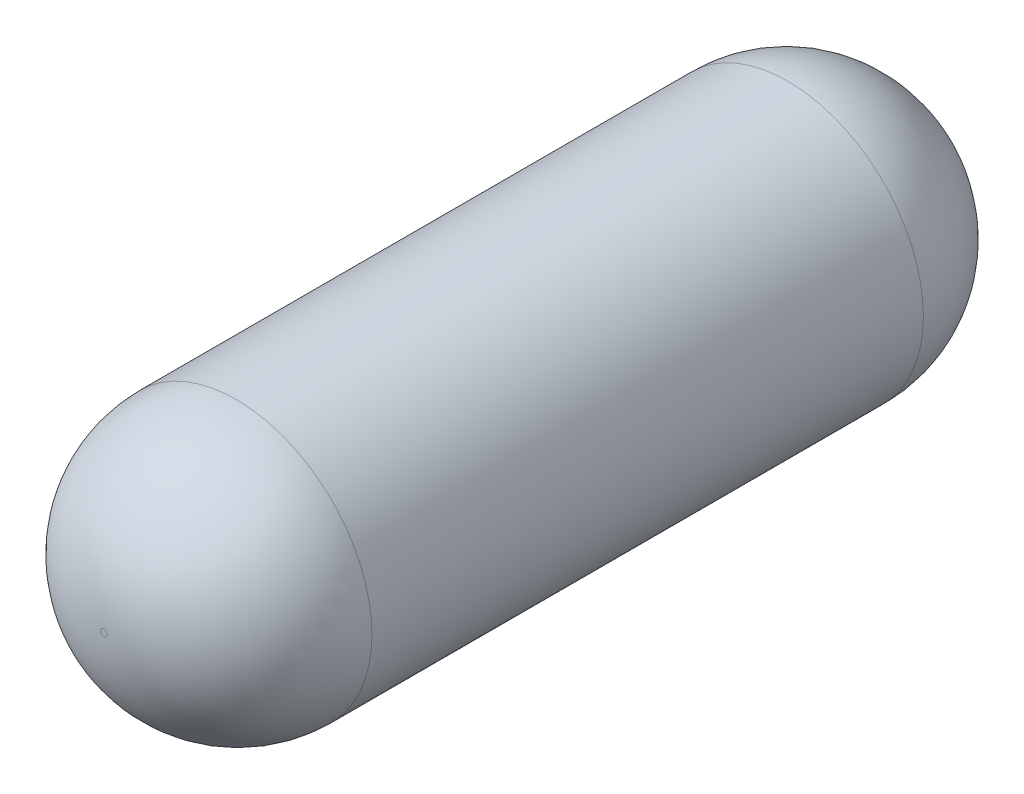
SolidWorks part; units mm, degrees
ref_plane "Front Plane" through (0, 0, 0) normal (0, 0, 1) x (1, 0, 0)
ref_plane "Top Plane" through (0, 0, 0) normal (0, 1, 0) x (1, 0, 0)
ref_plane "Right Plane" through (0, 0, 0) normal (1, 0, 0) x (0, 0, -1)
sketch "Sketch1" plane through (0, 0, 0) normal (0, 0, 1) x (1, 0, 0)
  circle A0 centre (0, 0) radius 61.5
  dimension "D1" = 123
extrude "Boss-Extrude1" add sketch "Sketch1" along normal blind 370
fillet "Fillet1" radius 60 2 edges at (61.5, 0, 0) (61.5, 0, 370)
